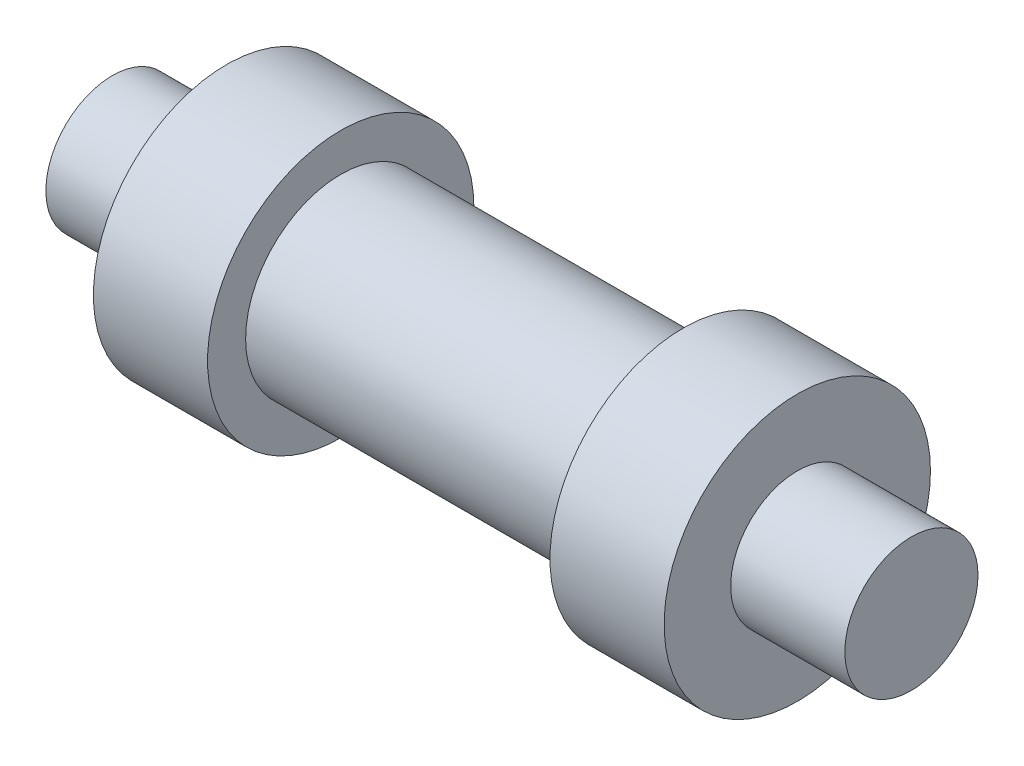
SolidWorks part; units mm, degrees
ref_plane "Front Plane" through (0, 0, 0) normal (0, 0, 1) x (1, 0, 0)
ref_plane "Top Plane" through (0, 0, 0) normal (0, 1, 0) x (1, 0, 0)
ref_plane "Right Plane" through (0, 0, 0) normal (1, 0, 0) x (0, 0, -1)
sketch "Sketch1" plane through (0, 0, 0) normal (0, 0, 1) x (1, 0, 0)
  line L0 (21, 0) -> (-21, 0)
  line L1 (-21, 0) -> (-21, 3.5)
  line L2 (-21, 3.5) -> (-15, 3.5)
  line L3 (-15, 3.5) -> (-15, 7)
  line L4 (-15, 7) -> (-9, 7)
  line L5 (-9, 7) -> (-9, 5)
  line L6 (-9, 5) -> (9, 5)
  line L7 (9, 5) -> (9, 7)
  line L8 (9, 7) -> (15, 7)
  line L9 (15, 7) -> (15, 3.5)
  line L10 (15, 3.5) -> (21, 3.5)
  line L11 (21, 3.5) -> (21, 0)
  point P4 (0, 0)
  dimension "D1" = 42
revolve "Revolve1" add sketch "Sketch1" angle 360 about L0
